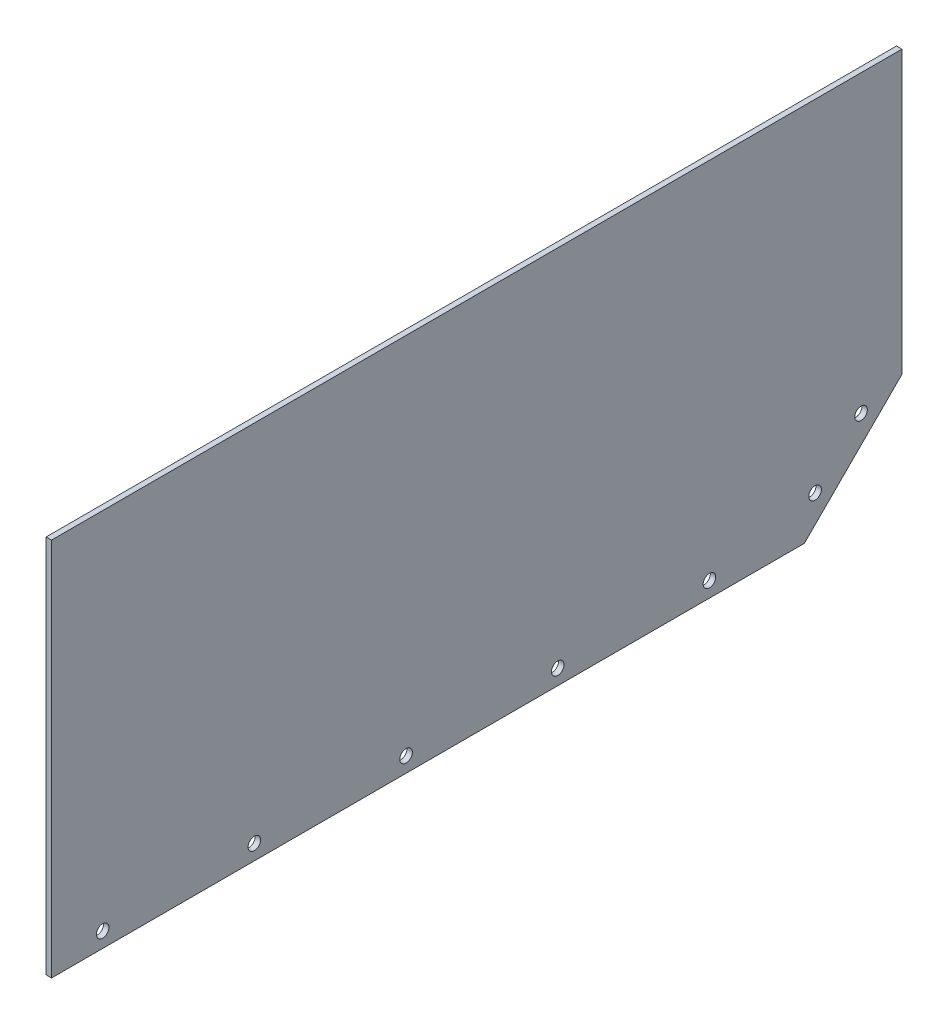
SolidWorks part; units mm, degrees
material "6061-T6 (SS)"
ref_plane "X-Y Datum" through (0, 0, 0) normal (0, 0, 1) x (1, 0, 0)
ref_plane "X-Z Datum" through (0, 0, 0) normal (0, 1, 0) x (1, 0, 0)
ref_plane "Y-Z Datum" through (0, 0, 0) normal (1, 0, 0) x (0, 0, -1)
sketch "Sketch1" plane through (0, 0, 0) normal (1, 0, 0) x (0, 0, -1)
  line L1 (-249.174, 82.55) -> (249.174, 82.55)
  line L2 (-249.174, 82.55) -> (-249.174, -82.55)
  line L3 (-249.174, -82.55) -> (249.174, -82.55)
  line L4 (249.174, 82.55) -> (249.174, -82.55)
  line L5 (-249.174, 82.55) -> (249.174, -82.55) construction
  line L6 (-249.174, -82.55) -> (249.174, 82.55) construction
  point P0 (0, 0)
  dimension "D1" = 165.1
  dimension "D2" = 498.348
extrude "Boss-Extrude1" add sketch "Sketch1" along normal mid plane 3.175
sketch "Sketch2" plane through (1.5875, 0, 0) normal (1, 0, 0) x (0, 0, -1)
  line L2 (249.174, -82.55) -> (192.024, -139.7)
  line L5 (-249.174, -82.55) -> (249.174, -82.55) construction
  line L6 (-249.174, -82.55) -> (249.174, -82.55)
  line L8 (192.024, -139.7) -> (-249.174, -139.7)
  line L9 (-249.174, -139.7) -> (-249.174, -82.55)
  line L11 (-249.174, 82.55) -> (-249.174, -82.55) construction
  line L12 (249.174, -82.55) -> (249.174, 82.55) construction
  dimension "D1" = 45
  dimension "D5" = 57.15
extrude "Boss-Extrude2" add sketch "Sketch2" against normal blind 3.175
sketch "Sketch3" plane through (-1.5875, 0, 0) normal (-1, 0, 0) x (0, 0, 1)
  line L0 (219.202, -139.7) -> (219.202, -130.81)
  line L1 (-192.024, -139.7) -> (249.174, -139.7) construction
  line L2 (219.202, -130.81) -> (249.174, -130.81)
  line L3 (249.174, 82.55) -> (249.174, -139.7) construction
  circle A0 centre (219.202, -130.81) radius 3.675
extrude "Cut-Extrude1" cut sketch "Sketch3" against normal through all contours L0 A0 L2 | L2 A0 L0
pattern_linear "LPattern1" count 5 spacing 88.9 along (0, 0, -1) of "Cut-Extrude1"
sketch "Sketch4" plane through (-1.5875, 0, 0) normal (-1, 0, 0) x (0, 0, 1)
  line L0 (-206.3924, -125.3316) -> (-198.3102, -117.2494)
  line L1 (-249.174, -82.55) -> (-192.024, -139.7) construction
  line L2 (-192.024, -139.7) -> (-183.9418, -131.6178)
  line L3 (-183.9418, -131.6178) -> (-198.3102, -117.2494)
  circle A0 centre (-198.3102, -117.2494) radius 3.675
extrude "Cut-Extrude2" cut sketch "Sketch4" against normal through all and the other way through all contours L3 A0 L0 | L0 A0 L3
pattern_linear "LPattern2" count 2 spacing 38.1 along (0, 0.7071, -0.7071) of "Cut-Extrude2"
